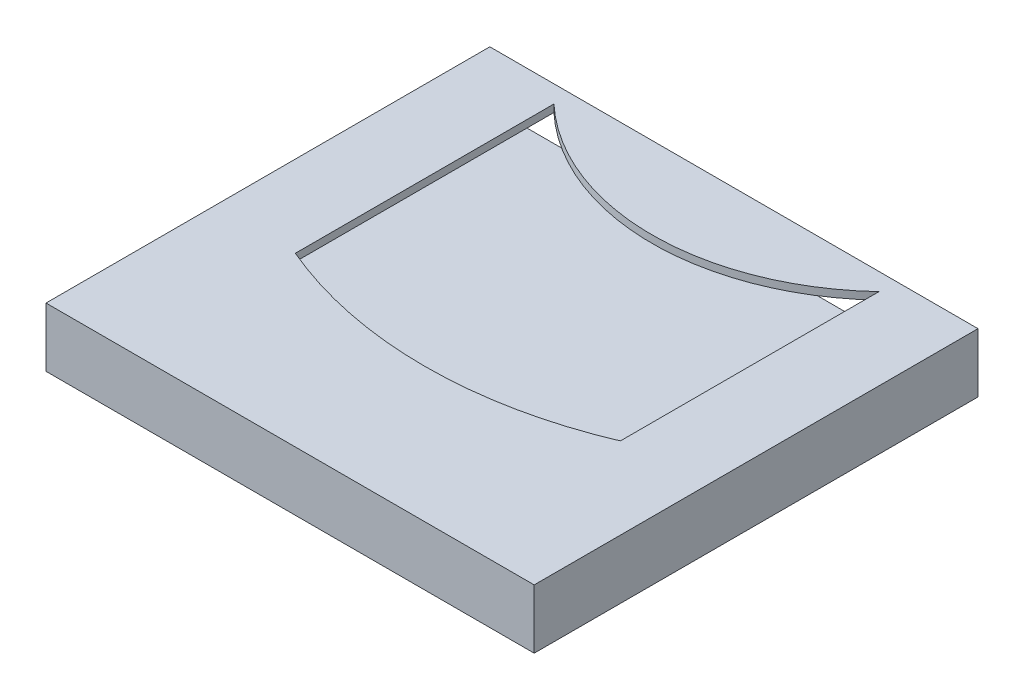
SolidWorks part; units mm, degrees
ref_plane "前视基准面" through (0, 0, 0) normal (0, 0, 1) x (1, 0, 0)
ref_plane "上视基准面" through (0, 0, 0) normal (0, 1, 0) x (1, 0, 0)
ref_plane "右视基准面" through (0, 0, 0) normal (1, 0, 0) x (0, 0, -1)
sketch "草图1" plane through (0, 0, 0) normal (0, 1, 0) x (1, 0, 0)
  line L0 (-59.7364, 0) -> (54.8847, 0) construction
  line L1 (0, 49.4265) -> (0, -41.8458) construction
  line L3 (-16.5, 15) -> (16.5, 15)
  line L4 (-16.5, 15) -> (-16.5, -15)
  line L5 (-16.5, -15) -> (16.5, -15)
  line L6 (16.5, 15) -> (16.5, -15)
  dimension "D1" = 33
  dimension "D2" = 30
extrude "拉伸1" add sketch "草图1" along normal blind 4
shell "抽壳1" thickness 0.5
sketch "草图2" plane through (0, 4, 0) normal (0, 1, 0) x (-1, 0, 0)
  line L0 (0, -18.1348) -> (0, 20.3596) construction
  line L1 (21.045, 3.6581) -> (-22.4579, 3.6581) construction
  line L2 (10.9856, -13.8199) -> (10.9856, 3.6581)
  line L3 (-10.9856, -13.8199) -> (-10.9856, 3.6581)
  line L4 (13.9317, -13.8199) -> (-11.9423, -13.8199) construction
  arc A0 (10.9856, -13.8199) -> (-10.9856, -13.8199) centre (0, -25.5256) ccw
  arc A1 (10.9856, 3.6581) -> (-10.9856, 3.6581) centre (0, -22.0857) ccw
extrude "切除-拉伸2" cut sketch "草图2" against normal blind 1
